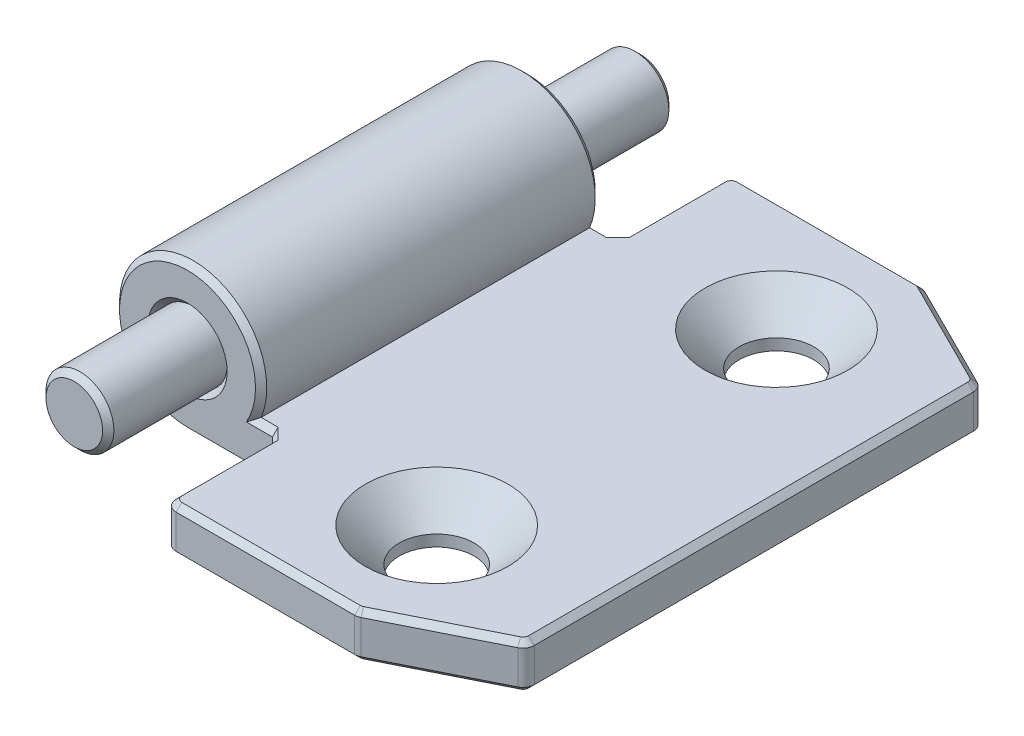
SolidWorks part; units mm, degrees
material "Galvanized Steel"
ref_plane "Front Plane" through (0, 0, 0) normal (0, 0, 1) x (1, 0, 0)
ref_plane "Top Plane" through (0, 0, 0) normal (0, 1, 0) x (1, 0, 0)
ref_plane "Right Plane" through (0, 0, 0) normal (1, 0, 0) x (0, 0, -1)
sketch "Sketch2" plane through (0, 0, 0) normal (0, 0, 1) x (1, 0, 0)
  line L0 (0, 0) -> (35, 0)
  line L1 (35, 0) -> (35, 4)
  line L2 (35, 4) -> (6, 4)
  arc A0 (6.0373, 4) -> (0.6699, 0) centre (0, 6.5) ccw
  arc A1 (6, 4) -> (0, 0) centre (0, 6.5) ccw
  circle A2 centre (0, 6.5) radius 3
  dimension "D1" = 4
  dimension "D3" = 13
  dimension "D4" = 6
  dimension "D2" = 35
extrude "Boss-Extrude1" add sketch "Sketch2" along normal mid plane 50 contours L2 A1 L0 L1 A2
sketch "Sketch3" plane through (0, 0, 0) normal (0, 1, 0) x (1, 0, 0)
  line L0 (35, -25) -> (35, 25) construction
  line L1 (8, 40) -> (-22, 40)
  line L2 (8, 40) -> (8, 15)
  line L3 (8, 15) -> (-22, 15)
  line L4 (-22, 40) -> (-22, 15)
  line L5 (8, -40) -> (-22, -40)
  line L6 (8, -40) -> (8, -15)
  line L7 (8, -15) -> (-22, -15)
  line L8 (-22, -40) -> (-22, -15)
  line L10 (6.5, 25) -> (-6.5, 25) construction
  line L11 (35, -25) -> (6, -25) construction
  line L12 (35, 20) -> (25, 25)
  line L14 (35, 25) -> (6, 25) construction
  line L15 (25, 25) -> (35, 25)
  line L16 (35, 25) -> (35, 20)
  line L17 (-7.1879, 0) -> (7.1879, 0) construction
  line L18 (35, -25) -> (35, -20)
  line L19 (25, -25) -> (35, -25)
  line L20 (35, -20) -> (25, -25)
  dimension "D1" = 27
  dimension "D2" = 10
  dimension "D3" = 10
  dimension "D4" = 30
  dimension "D5" = 25
  dimension "D6" = 10
  dimension "D7" = 5
extrude "Cut-Extrude1" cut sketch "Sketch3" along normal through all
sketch "Sketch4" plane through (0, 4, 0) normal (0, 1, 0) x (1, 0, 0)
  point P0 (22, 15)
  point P1 (22, -15)
  dimension "D1" = 30
  dimension "D2" = 15
  dimension "D3" = 22
hole_wizard "CSK for M6 Flat Head Machine Screw1" positions "Sketch4" profile "Sketch5" countersink size "M6" standard "ANSI Metric"
sketch "Sketch5" plane through (22, 4, -15) normal (1, 0, 0) x (0, 0, 1)
  line L0 (0, 0) -> (0, 40)
  line L1 (0, 40) -> (3.3, 38.0172)
  line L2 (3.3, 38.0172) -> (3.3, 3)
  line L3 (3.3, 3) -> (6.3, 0)
  line L5 (6.3, 0) -> (0, 0)
  line L6 (-3.3, 3) -> (-6.3, 0) construction
  line L10 (0, 40) -> (-3.3, 38.0172) construction
  line L11 (0, -6.35) -> (0, 107.95) construction
  dimension "Hole Dia." = 6.6
  dimension "Hole Depth" = 40
  dimension "Near C'Sink Dia." = 12.6
  dimension "Near C'Sink Angle" = 90
  dimension "Drill Angle" = 118
fillet "Fillet1" radius 1 6 edges at (25, 2, -25) (35, 2, -20) (35, 2, 20) (25, 2, 25) (8, 2, 25) (8, 2, -25)
chamfer "Chamfer1" distance 0.5 angle 45 36 edges at (8, 2, 15) (4, 0, 15) (-3.6056, 11.9083, 15) (7, 4, 15) (3, 6.5, 15) (8, 0, 19.5) (8, 4, 19.5) (8.2929, 0, 24.7071) (8.2929, 4, 24.7071) (16.882, 0, 25) (16.882, 4, 25) (24.9937, 0, 24.9732) (24.9937, 4, 24.9732) (29.8292, 0, 22.5854) (29.8292, 4, 22.5854) (34.8507, 0, 19.9077) (34.8507, 4, 19.9077) (35, 0, 0) (35, 4, 0) (34.8507, 0, -19.9077) (34.8507, 4, -19.9077) (29.8292, 0, -22.5854) (29.8292, 4, -22.5854) (24.9937, 0, -24.9732) (24.9937, 4, -24.9732) (16.882, 0, -25) (16.882, 4, -25) (8.2929, 0, -24.7071) (8.2929, 4, -24.7071) (8, 0, -19.5) (8, 4, -19.5) (-3.6056, 11.9083, -15) (4, 0, -15) (8, 2, -15) (7, 4, -15) (-3, 6.5, -15)
sketch "Sketch6" plane through (0, 0, 0) normal (0, 0, 1) x (1, 0, 0)
  circle A0 centre (0, 6.5) radius 3
  dimension "D1" = 6
extrude "Boss-Extrude2" add sketch "Sketch6" along normal mid plane 50 separate body
chamfer "Chamfer2" distance 0.5 angle 45 2 edges at (3, 6.5, -25) (3, 6.5, 25)
equation "\"D3@Sketch3\"=\"D2@Sketch3\""
equation "\"D2@Sketch4\"=\"D1@Sketch4\"/2"
